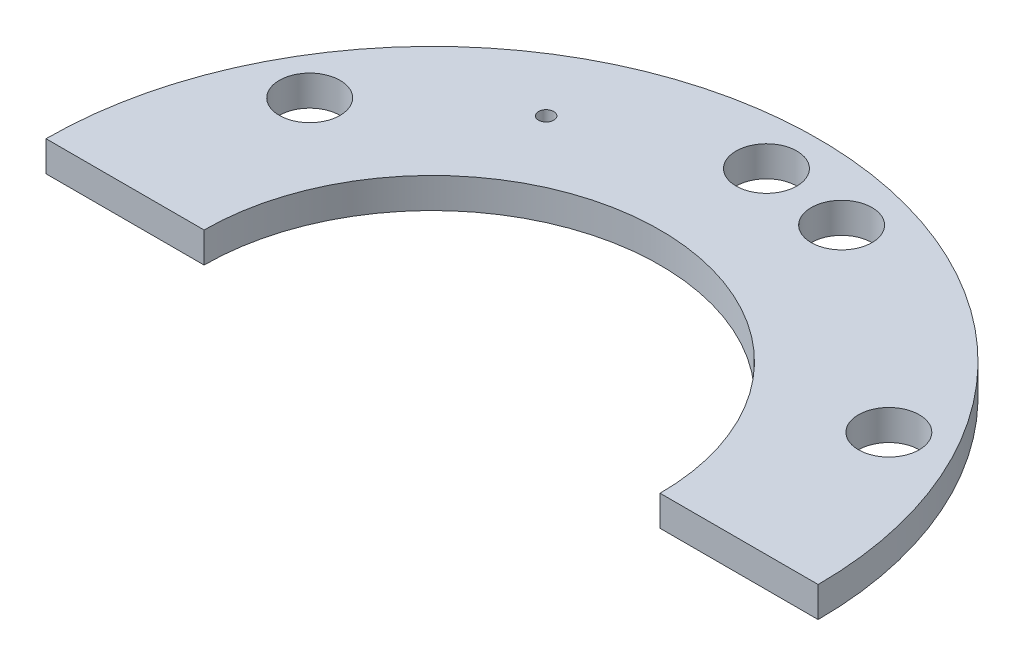
SolidWorks part; units mm, degrees
material "ABS"
ref_plane "Front Plane" through (0, 0, 0) normal (0, 0, 1) x (1, 0, 0)
ref_plane "Top Plane" through (0, 0, 0) normal (0, 1, 0) x (1, 0, 0)
ref_plane "Right Plane" through (0, 0, 0) normal (1, 0, 0) x (0, 0, -1)
sketch "Sketch1" plane through (0, 0, 0) normal (0, 1, 0) x (1, 0, 0)
  circle A0 centre (0, 0) radius 12.7
  dimension "D1" = 25.4
extrude "Boss-Extrude1" add sketch "Sketch1" along normal blind 1
sketch "Sketch19" plane through (0, 1, 0) normal (0, 1, 0) x (1, 0, 0)
  circle A0 centre (0, 11) radius 1
  circle A1 centre (9.5263, 5.5) radius 1
  circle A2 centre (9.5263, -5.5) radius 1
  circle A3 centre (0, -11) radius 1
  circle A4 centre (-9.5263, -5.5) radius 1
  circle A5 centre (-9.5263, 5.5) radius 1
  point P13 (0, 0)
  dimension "D1" = 2
  dimension "D2" = 11
  dimension "D3" = 6
extrude "Cut-Extrude1" cut sketch "Sketch19" against normal through all both and the other way through all
sketch "Sketch20" plane through (0, 1, 0) normal (0, 1, 0) x (1, 0, 0)
  circle A0 centre (0, 0) radius 7.5
  dimension "D1" = 15
extrude "Cut-Extrude2" cut sketch "Sketch20" against normal through all both and the other way through all
sketch "Sketch21" plane through (0, 0, 0) normal (0, 0, 1) x (1, 0, 0)
  line L1 (-36.7533, 32.3113) -> (29.1209, 32.3113)
  line L2 (-36.7533, 32.3113) -> (-36.7533, -19.668)
  line L3 (-36.7533, -19.668) -> (29.1209, -19.668)
  line L4 (29.1209, 32.3113) -> (29.1209, -19.668)
extrude "Cut-Extrude3" cut sketch "Sketch21" along normal through all
sketch "Sketch22" plane through (0, 1, 0) normal (0, 1, 0) x (1, 0, 0)
  line L0 (-5.125, 8.8768) -> (0, 0) construction
  line L1 (0, 0) -> (3.9475, 14.7323) construction
  line L2 (-9.5263, 5.5) -> (0, 11)
  circle A0 centre (-5.125, 8.8768) radius 0.25
  circle A2 centre (2.847, 10.6252) radius 1
  point P14 (-4.7631, 8.25)
  dimension "D1" = 0.5
  dimension "D2" = 10.25
  dimension "D3" = 0
  dimension "D5" = 2
  dimension "D4" = 45
  dimension "D6" = 11
extrude "Cut-Extrude4" cut sketch "Sketch22" against normal through all both and the other way through all contours L2 A0 | L2 A0 | A2
